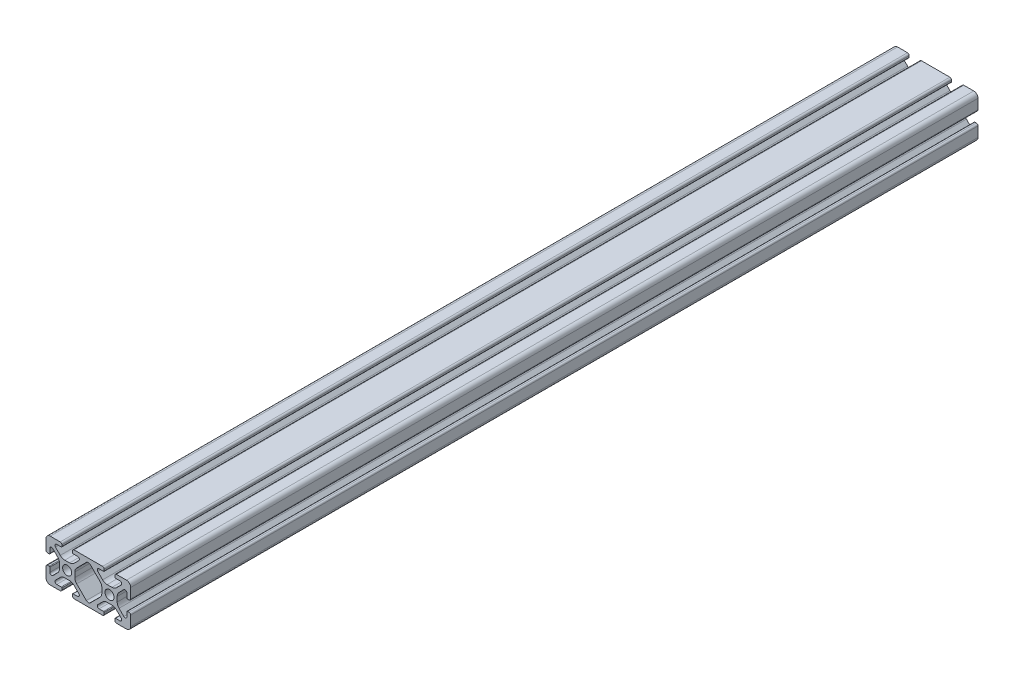
SolidWorks part; units mm, degrees
material "6061 Alloy"
ref_plane "Front Plane" through (0, 0, 0) normal (0, 0, 1) x (1, 0, 0)
ref_plane "Top Plane" through (0, 0, 0) normal (0, 1, 0) x (1, 0, 0)
ref_plane "Right Plane" through (0, 0, 0) normal (1, 0, 0) x (0, 0, -1)
sketch "Sketch1" plane through (0, 0, 0) normal (0, 0, 1) x (1, 0, 0)
  line L2 (-19.9898, 7.9883) -> (-19.9898, 3.2893)
  line L3 (-17.9832, 9.9949) -> (-13.2842, 9.9949)
  line L4 (-12.4968, 9.2075) -> (-12.4968, 8.4963)
  line L5 (-12.8016, 8.1915) -> (-14.9098, 8.1915)
  line L6 (-15.5025, 6.7606) -> (-13.2477, 4.5058)
  line L7 (-16.7555, 5.5076) -> (-14.5007, 3.2528)
  line L8 (-18.1864, 4.9149) -> (-18.1864, 2.8067)
  line L9 (-18.4912, 2.5019) -> (-19.2024, 2.5019)
  line L11 (-11.1283, 3.6279) -> (-8.8615, 3.6279)
  line L12 (-13.6228, 1.1334) -> (-13.6228, -1.1334)
  line L13 (0, 9.9949) -> (-6.7056, 9.9949)
  line L14 (-7.493, 9.2075) -> (-7.493, 8.4963)
  line L15 (-7.1882, 8.1915) -> (-5.08, 8.1915)
  line L16 (-6.367, 1.1334) -> (-6.367, -1.1334)
  line L17 (-4.4873, 6.7606) -> (-6.7421, 4.5058)
  line L18 (-0.9396, 7.8023) -> (-5.4891, 3.2528)
  line L19 (-18.4912, -2.5019) -> (-19.2024, -2.5019)
  line L20 (-18.1864, -4.9149) -> (-18.1864, -2.8067)
  line L21 (-16.7555, -5.5076) -> (-14.5007, -3.2528)
  line L22 (-15.5025, -6.7606) -> (-13.2477, -4.5058)
  line L23 (-12.8016, -8.1915) -> (-14.9098, -8.1915)
  line L24 (-12.4968, -9.2075) -> (-12.4968, -8.4963)
  line L25 (-17.9832, -9.9949) -> (-13.2842, -9.9949)
  line L26 (-19.9898, -7.9883) -> (-19.9898, -3.2893)
  line L27 (0, -9.9949) -> (-6.7056, -9.9949)
  line L28 (-7.493, -9.2075) -> (-7.493, -8.4963)
  line L29 (-7.1882, -8.1915) -> (-5.08, -8.1915)
  line L30 (-4.4873, -6.7606) -> (-6.7421, -4.5058)
  line L31 (-0.9396, -7.8023) -> (-5.4891, -3.2528)
  line L32 (-11.1283, -3.6279) -> (-8.8615, -3.6279)
  line L34 (11.1283, -3.6279) -> (8.8615, -3.6279)
  line L35 (0.9396, -7.8023) -> (5.4891, -3.2528)
  line L36 (4.4873, -6.7606) -> (6.7421, -4.5058)
  line L37 (7.1882, -8.1915) -> (5.08, -8.1915)
  line L38 (7.493, -9.2075) -> (7.493, -8.4963)
  line L39 (0, -9.9949) -> (6.7056, -9.9949)
  line L40 (19.9898, -7.9883) -> (19.9898, -3.2893)
  line L41 (17.9832, -9.9949) -> (13.2842, -9.9949)
  line L42 (12.4968, -9.2075) -> (12.4968, -8.4963)
  line L43 (12.8016, -8.1915) -> (14.9098, -8.1915)
  line L44 (15.5025, -6.7606) -> (13.2477, -4.5058)
  line L45 (16.7555, -5.5076) -> (14.5007, -3.2528)
  line L46 (18.1864, -4.9149) -> (18.1864, -2.8067)
  line L47 (18.4912, -2.5019) -> (19.2024, -2.5019)
  line L48 (0.9396, 7.8023) -> (5.4891, 3.2528)
  line L49 (4.4873, 6.7606) -> (6.7421, 4.5058)
  line L50 (6.367, 1.1334) -> (6.367, -1.1334)
  line L51 (7.1882, 8.1915) -> (5.08, 8.1915)
  line L52 (7.493, 9.2075) -> (7.493, 8.4963)
  line L53 (0, 9.9949) -> (6.7056, 9.9949)
  line L54 (13.6228, 1.1334) -> (13.6228, -1.1334)
  line L55 (11.1283, 3.6279) -> (8.8615, 3.6279)
  line L56 (18.4912, 2.5019) -> (19.2024, 2.5019)
  line L57 (18.1864, 4.9149) -> (18.1864, 2.8067)
  line L58 (16.7555, 5.5076) -> (14.5007, 3.2528)
  line L59 (15.5025, 6.7606) -> (13.2477, 4.5058)
  line L60 (12.8016, 8.1915) -> (14.9098, 8.1915)
  line L61 (12.4968, 9.2075) -> (12.4968, 8.4963)
  line L62 (17.9832, 9.9949) -> (13.2842, 9.9949)
  line L63 (19.9898, 7.9883) -> (19.9898, 3.2893)
  circle A0 centre (-9.9949, 0) radius 2.1463
  arc A1 (-19.9898, 7.9883) -> (-17.9832, 9.9949) centre (-17.9832, 7.9883) cw
  arc A2 (-16.7555, 5.5076) -> (-18.1864, 4.9149) centre (-17.3482, 4.9149) ccw
  arc A3 (-14.9098, 8.1915) -> (-15.5025, 6.7606) centre (-14.9098, 7.3533) ccw
  arc A4 (-13.2842, 9.9949) -> (-12.4968, 9.2075) centre (-13.2842, 9.2075) cw
  arc A5 (-19.9898, 3.2893) -> (-19.2024, 2.5019) centre (-19.2024, 3.2893) ccw
  arc A6 (-18.1864, 2.8067) -> (-18.4912, 2.5019) centre (-18.4912, 2.8067) cw
  arc A7 (-12.4968, 8.4963) -> (-12.8016, 8.1915) centre (-12.8016, 8.4963) cw
  arc A8 (-11.1283, 3.6279) -> (-13.2477, 4.5058) centre (-11.1283, 6.6251) cw
  arc A9 (-13.6228, 1.1334) -> (-14.5007, 3.2528) centre (-16.62, 1.1334) ccw
  arc A10 (0.9396, 7.8023) -> (-0.9396, 7.8023) centre (0, 6.8627) ccw
  arc A11 (-0.9396, -7.8023) -> (0.9396, -7.8023) centre (0, -6.8627) ccw
  arc A12 (-6.7056, 9.9949) -> (-7.493, 9.2075) centre (-6.7056, 9.2075) ccw
  arc A13 (-7.493, 8.4963) -> (-7.1882, 8.1915) centre (-7.1882, 8.4963) ccw
  arc A14 (-8.8615, 3.6279) -> (-6.7421, 4.5058) centre (-8.8615, 6.6251) ccw
  arc A15 (-6.367, 1.1334) -> (-5.4891, 3.2528) centre (-3.3698, 1.1334) cw
  arc A16 (-5.08, 8.1915) -> (-4.4873, 6.7606) centre (-5.08, 7.3533) cw
  arc A17 (-13.6228, -1.1334) -> (-14.5007, -3.2528) centre (-16.62, -1.1334) cw
  arc A18 (-11.1283, -3.6279) -> (-13.2477, -4.5058) centre (-11.1283, -6.6251) ccw
  arc A19 (-12.4968, -8.4963) -> (-12.8016, -8.1915) centre (-12.8016, -8.4963) ccw
  arc A20 (-18.1864, -2.8067) -> (-18.4912, -2.5019) centre (-18.4912, -2.8067) ccw
  arc A21 (-19.9898, -3.2893) -> (-19.2024, -2.5019) centre (-19.2024, -3.2893) cw
  arc A22 (-13.2842, -9.9949) -> (-12.4968, -9.2075) centre (-13.2842, -9.2075) ccw
  arc A23 (-14.9098, -8.1915) -> (-15.5025, -6.7606) centre (-14.9098, -7.3533) cw
  arc A24 (-16.7555, -5.5076) -> (-18.1864, -4.9149) centre (-17.3482, -4.9149) cw
  arc A25 (-19.9898, -7.9883) -> (-17.9832, -9.9949) centre (-17.9832, -7.9883) ccw
  arc A26 (-5.08, -8.1915) -> (-4.4873, -6.7606) centre (-5.08, -7.3533) ccw
  arc A27 (-6.7056, -9.9949) -> (-7.493, -9.2075) centre (-6.7056, -9.2075) cw
  arc A28 (-7.493, -8.4963) -> (-7.1882, -8.1915) centre (-7.1882, -8.4963) cw
  arc A29 (-8.8615, -3.6279) -> (-6.7421, -4.5058) centre (-8.8615, -6.6251) cw
  arc A30 (-6.367, -1.1334) -> (-5.4891, -3.2528) centre (-3.3698, -1.1334) ccw
  arc A31 (6.367, -1.1334) -> (5.4891, -3.2528) centre (3.3698, -1.1334) cw
  arc A32 (8.8615, -3.6279) -> (6.7421, -4.5058) centre (8.8615, -6.6251) ccw
  arc A33 (7.493, -8.4963) -> (7.1882, -8.1915) centre (7.1882, -8.4963) ccw
  arc A34 (6.7056, -9.9949) -> (7.493, -9.2075) centre (6.7056, -9.2075) ccw
  arc A35 (5.08, -8.1915) -> (4.4873, -6.7606) centre (5.08, -7.3533) cw
  arc A36 (19.9898, -7.9883) -> (17.9832, -9.9949) centre (17.9832, -7.9883) cw
  arc A37 (16.7555, -5.5076) -> (18.1864, -4.9149) centre (17.3482, -4.9149) ccw
  arc A38 (14.9098, -8.1915) -> (15.5025, -6.7606) centre (14.9098, -7.3533) ccw
  arc A39 (13.2842, -9.9949) -> (12.4968, -9.2075) centre (13.2842, -9.2075) cw
  arc A40 (19.9898, -3.2893) -> (19.2024, -2.5019) centre (19.2024, -3.2893) ccw
  arc A41 (18.1864, -2.8067) -> (18.4912, -2.5019) centre (18.4912, -2.8067) cw
  arc A42 (12.4968, -8.4963) -> (12.8016, -8.1915) centre (12.8016, -8.4963) cw
  arc A43 (11.1283, -3.6279) -> (13.2477, -4.5058) centre (11.1283, -6.6251) cw
  arc A44 (13.6228, -1.1334) -> (14.5007, -3.2528) centre (16.62, -1.1334) ccw
  arc A45 (5.08, 8.1915) -> (4.4873, 6.7606) centre (5.08, 7.3533) ccw
  arc A46 (6.367, 1.1334) -> (5.4891, 3.2528) centre (3.3698, 1.1334) ccw
  arc A47 (8.8615, 3.6279) -> (6.7421, 4.5058) centre (8.8615, 6.6251) cw
  arc A48 (7.493, 8.4963) -> (7.1882, 8.1915) centre (7.1882, 8.4963) cw
  arc A49 (6.7056, 9.9949) -> (7.493, 9.2075) centre (6.7056, 9.2075) cw
  arc A50 (13.6228, 1.1334) -> (14.5007, 3.2528) centre (16.62, 1.1334) cw
  arc A51 (11.1283, 3.6279) -> (13.2477, 4.5058) centre (11.1283, 6.6251) ccw
  arc A52 (12.4968, 8.4963) -> (12.8016, 8.1915) centre (12.8016, 8.4963) ccw
  arc A53 (18.1864, 2.8067) -> (18.4912, 2.5019) centre (18.4912, 2.8067) ccw
  arc A54 (19.9898, 3.2893) -> (19.2024, 2.5019) centre (19.2024, 3.2893) cw
  arc A55 (13.2842, 9.9949) -> (12.4968, 9.2075) centre (13.2842, 9.2075) ccw
  arc A56 (14.9098, 8.1915) -> (15.5025, 6.7606) centre (14.9098, 7.3533) cw
  arc A57 (16.7555, 5.5076) -> (18.1864, 4.9149) centre (17.3482, 4.9149) cw
  arc A58 (19.9898, 7.9883) -> (17.9832, 9.9949) centre (17.9832, 7.9883) ccw
  circle A59 centre (9.9949, 0) radius 2.1463
  point P186 (9.9949, 3.6279)
extrude "Boss-Extrude1" add sketch "Sketch1" along normal mid plane 400
